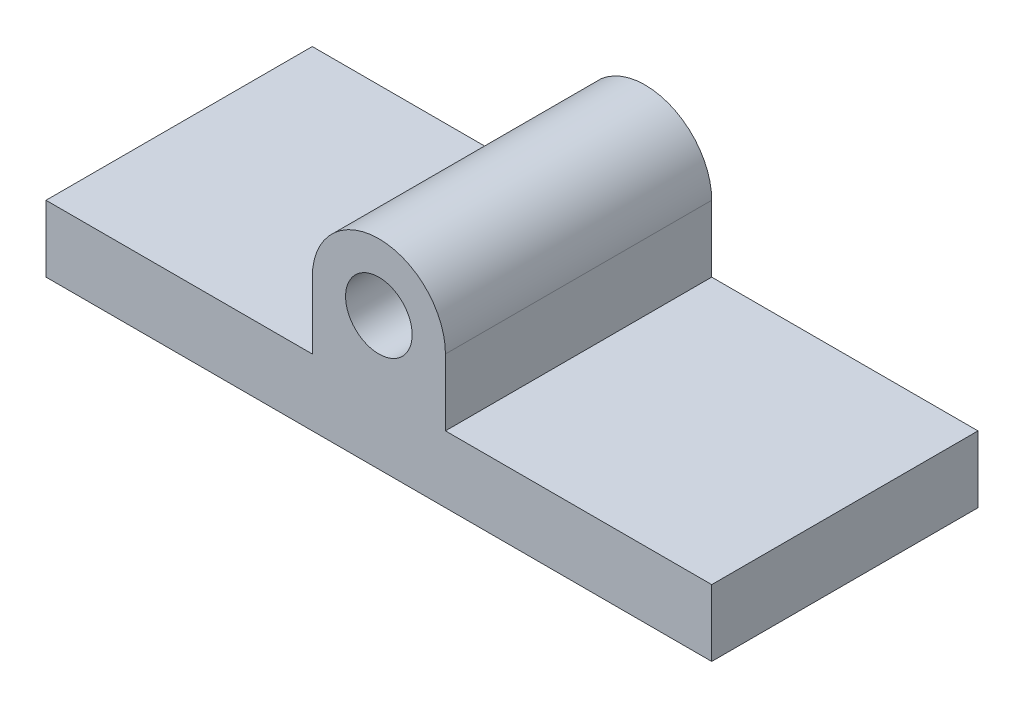
SolidWorks part; units mm, degrees
ref_plane "前视基准面" through (0, 0, 0) normal (0, 0, 1) x (1, 0, 0)
ref_plane "上视基准面" through (0, 0, 0) normal (0, 1, 0) x (1, 0, 0)
ref_plane "右视基准面" through (0, 0, 0) normal (1, 0, 0) x (0, 0, -1)
other "Configuration Table"
sketch "草图1" plane through (0, 0, 0) normal (0, 0, 1) x (1, 0, 0)
  line L0 (0, 0) -> (0, 24.9966) construction
  line L1 (-25, 0) -> (25, 0)
  line L2 (25, 0) -> (25, 5)
  line L3 (25, 5) -> (-25, 5)
  line L4 (-25, 0) -> (-25, 5)
  point P7 (0, 5)
  dimension "D1" = 50
  dimension "D2" = 5
extrude "凸台-拉伸1" add sketch "草图1" along normal blind 20
sketch "草图2" plane through (0, 0, 20) normal (0, 0, 1) x (1, 0, 0)
  line L0 (0, 0) -> (0, 11.445) construction
  line L1 (-25, 0) -> (25, 0) construction
  line L2 (-5, 10) -> (-5, 5)
  line L3 (25, 5) -> (-25, 5) construction
  line L4 (-5, 5) -> (5, 5)
  line L5 (5, 5) -> (5, 10)
  arc A0 (5, 10) -> (-5, 10) centre (0, 10) ccw
  point P11 (9.4245, 5)
  dimension "D1" = 10
  dimension "D2" = 10
extrude "凸台-拉伸2" add sketch "草图2" against normal blind 20
sketch "草图3" plane through (0, 0, 20) normal (0, 0, 1) x (1, 0, 0)
  circle A0 centre (0, 10) radius 2.5
  dimension "D1" = 5
extrude "切除-拉伸1" cut sketch "草图3" against normal blind 20
